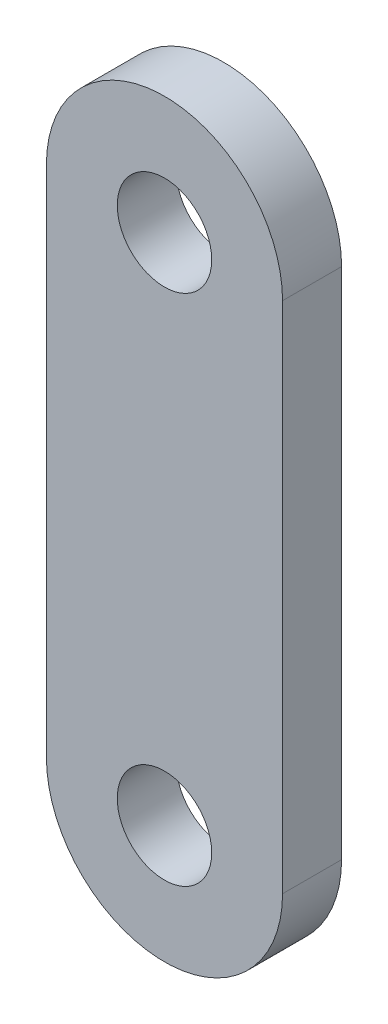
SolidWorks part; units mm, degrees
ref_plane "Front Plane" through (0, 0, 0) normal (0, 0, 1) x (1, 0, 0)
ref_plane "Top Plane" through (0, 0, 0) normal (0, 1, 0) x (1, 0, 0)
ref_plane "Right Plane" through (0, 0, 0) normal (1, 0, 0) x (0, 0, -1)
sketch "Sketch2" plane through (0, 0, 0) normal (0, 0, 1) x (1, 0, 0)
  line L0 (0, 0) -> (0, 43.5) construction
  line L1 (-10, 0) -> (-10, 43.5)
  line L2 (10, 0) -> (10, 43.5)
  arc A0 (-10, 0) -> (10, 0) centre (0, 0) ccw
  arc A1 (10, 43.5) -> (-10, 43.5) centre (0, 43.5) ccw
  circle A2 centre (0, 43.5) radius 4
  circle A3 centre (0, 0) radius 4
  point P3 (0, 21.75)
  dimension "D2" = 20
  dimension "D3" = 8
  dimension "D1" = 43.5
extrude "Boss-Extrude1" add sketch "Sketch2" along normal blind 5
